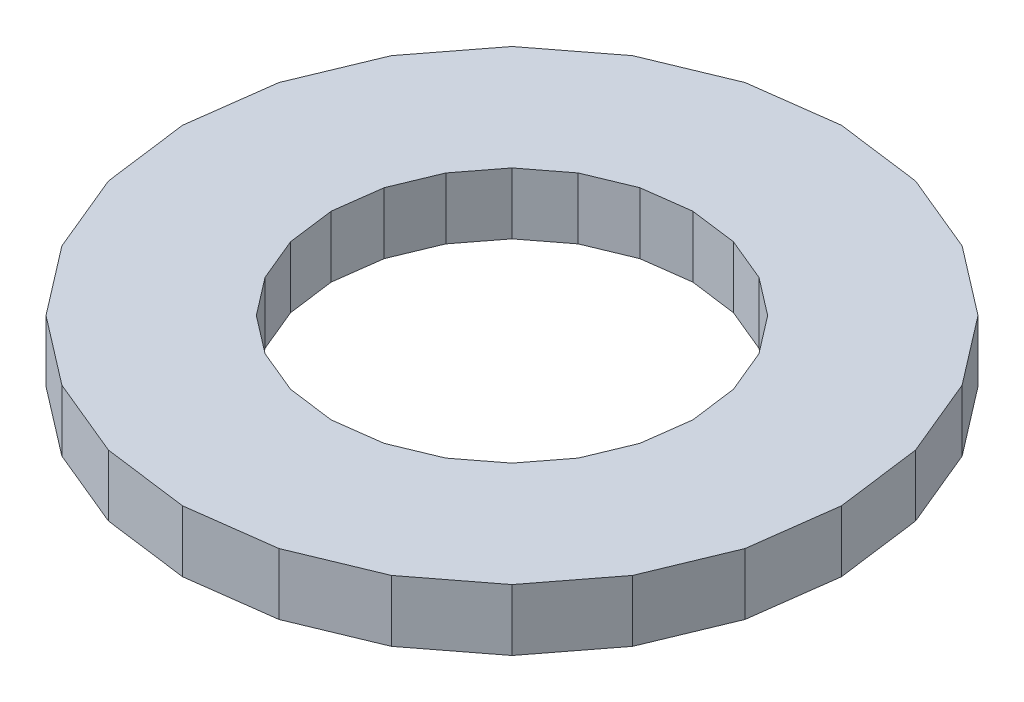
SolidWorks part; units mm, degrees
ref_plane "Front Plane" through (0, 0, 0) normal (0, 0, 1) x (1, 0, 0)
ref_plane "Top Plane" through (0, 0, 0) normal (0, 1, 0) x (1, 0, 0)
ref_plane "Right Plane" through (0, 0, 0) normal (1, 0, 0) x (0, 0, -1)
sketch "Sketch1" plane through (0, 0, 0) normal (0, 1, 0) x (1, 0, 0)
  line L0 (0, 0) -> (-56.0489, 0) construction
  line L1 (-56.0489, 0) -> (-54.1391, -14.5065)
  line L2 (-54.1391, -14.5065) -> (-48.5398, -28.0244)
  line L3 (-48.5398, -28.0244) -> (-39.6325, -39.6325)
  line L4 (-39.6325, -39.6325) -> (-28.0244, -48.5398)
  line L5 (-28.0244, -48.5398) -> (-14.5065, -54.1391)
  line L6 (-14.5065, -54.1391) -> (0, -56.0489)
  line L7 (0, -56.0489) -> (14.5065, -54.1391)
  line L8 (14.5065, -54.1391) -> (28.0244, -48.5398)
  line L9 (28.0244, -48.5398) -> (39.6325, -39.6325)
  line L10 (39.6325, -39.6325) -> (48.5398, -28.0244)
  line L11 (48.5398, -28.0244) -> (54.1391, -14.5065)
  line L12 (54.1391, -14.5065) -> (56.0489, 0)
  line L13 (56.0489, 0) -> (54.1391, 14.5065)
  line L14 (54.1391, 14.5065) -> (48.5398, 28.0244)
  line L15 (48.5398, 28.0244) -> (39.6325, 39.6325)
  line L16 (39.6325, 39.6325) -> (28.0244, 48.5398)
  line L17 (28.0244, 48.5398) -> (14.5065, 54.1391)
  line L18 (14.5065, 54.1391) -> (0, 56.0489)
  line L19 (0, 56.0489) -> (-14.5065, 54.1391)
  line L20 (-14.5065, 54.1391) -> (-28.0244, 48.5398)
  line L21 (-28.0244, 48.5398) -> (-39.6325, 39.6325)
  line L22 (-39.6325, 39.6325) -> (-48.5398, 28.0244)
  line L23 (-48.5398, 28.0244) -> (-54.1391, 14.5065)
  line L24 (-54.1391, 14.5065) -> (-56.0489, 0)
  line L25 (-102.1634, 0) -> (-98.6823, -26.4418)
  line L26 (-98.6823, -26.4418) -> (-88.4761, -51.0817)
  line L27 (-88.4761, -51.0817) -> (-72.2404, -72.2404)
  line L28 (-72.2404, -72.2404) -> (-51.0817, -88.4761)
  line L29 (-51.0817, -88.4761) -> (-26.4418, -98.6823)
  line L30 (-26.4418, -98.6823) -> (0, -102.1634)
  line L31 (0, -102.1634) -> (26.4418, -98.6823)
  line L32 (26.4418, -98.6823) -> (51.0817, -88.4761)
  line L33 (51.0817, -88.4761) -> (72.2404, -72.2404)
  line L34 (72.2404, -72.2404) -> (88.4761, -51.0817)
  line L35 (88.4761, -51.0817) -> (98.6823, -26.4418)
  line L36 (98.6823, -26.4418) -> (102.1634, 0)
  line L37 (102.1634, 0) -> (98.6823, 26.4418)
  line L38 (98.6823, 26.4418) -> (88.4761, 51.0817)
  line L39 (88.4761, 51.0817) -> (72.2404, 72.2404)
  line L40 (72.2404, 72.2404) -> (51.0817, 88.4761)
  line L41 (51.0817, 88.4761) -> (26.4418, 98.6823)
  line L42 (26.4418, 98.6823) -> (0, 102.1634)
  line L43 (0, 102.1634) -> (-26.4418, 98.6823)
  line L44 (-26.4418, 98.6823) -> (-51.0817, 88.4761)
  line L45 (-51.0817, 88.4761) -> (-72.2404, 72.2404)
  line L46 (-72.2404, 72.2404) -> (-88.4761, 51.0817)
  line L47 (-88.4761, 51.0817) -> (-98.6823, 26.4418)
  line L48 (-98.6823, 26.4418) -> (-102.1634, 0)
  line L49 (-56.0489, 0) -> (-102.1634, 0) construction
  circle A1 centre (0, 0) radius 55.5694 construction
  circle A2 centre (0, 0) radius 101.2894 construction
  dimension "D1" = 45.72
  dimension "D2" = 26.67
extrude "Boss-Extrude1" add sketch "Sketch1" along normal blind 19.05
